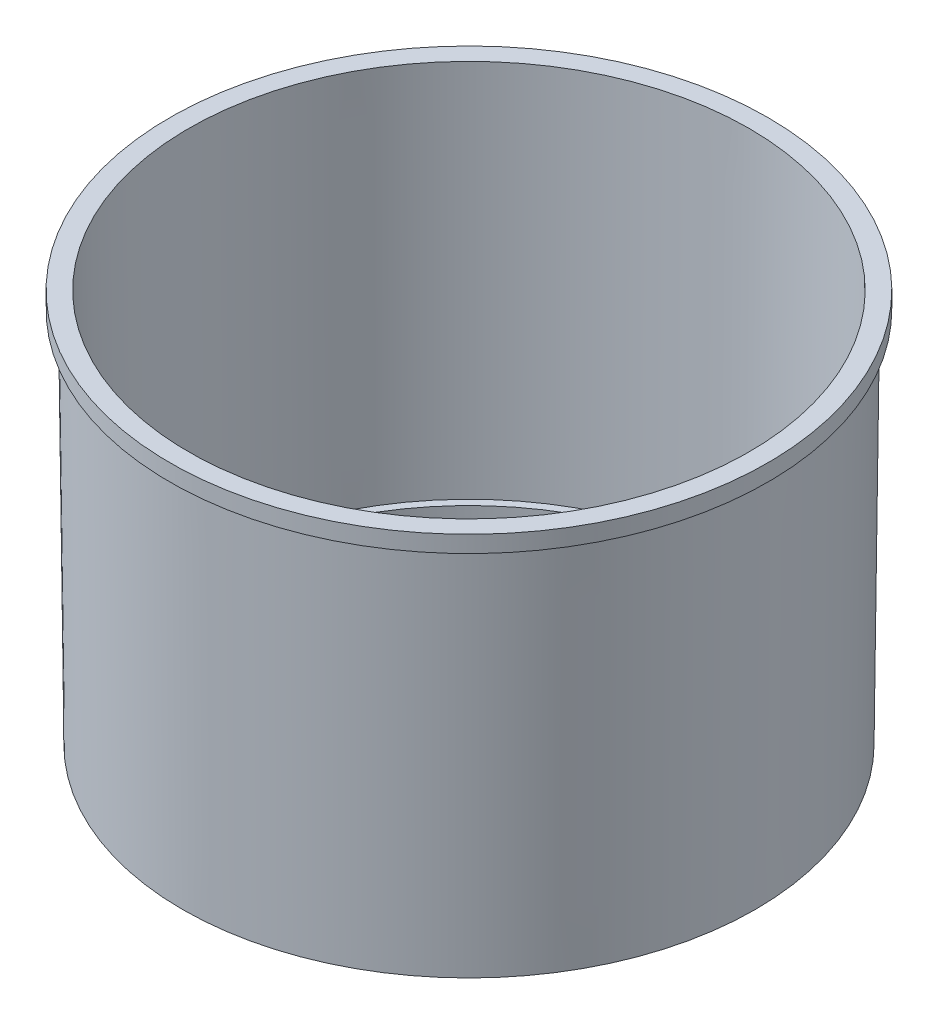
SolidWorks part; units mm, degrees
ref_plane "前视基准面" through (0, 0, 0) normal (0, 0, 1) x (1, 0, 0)
ref_plane "上视基准面" through (0, 0, 0) normal (0, 1, 0) x (1, 0, 0)
ref_plane "右视基准面" through (0, 0, 0) normal (1, 0, 0) x (0, 0, -1)
ref_axis "基准轴1" through (0, -2.25, 0) along (0, 1, 0)
ref_plane "基准面1" through (0, 47, 0) normal (0, 1, 0) x (1, 0, 0)
sketch "草图3" plane through (0, 0, 0) normal (0, 0, 1) x (1, 0, 0)
  line L0 (-34.7288, 45) -> (-34.25, 0)
  line L1 (55, 47) -> (-55, 47) construction
  line L2 (55, 0) -> (-55, 0) construction
  line L4 (-33.0212, 2) -> (-33.5, 47)
  line L6 (0, -55) -> (0, 55) construction
  line L7 (-33.0212, 2) -> (-32.1, 2)
  line L8 (-32.1, 2) -> (-32.1, 0)
  line L11 (-35.75, 47) -> (-35.75, 45)
  line L12 (-35.75, 45) -> (-34.7288, 45)
  line L13 (-32.1, 0) -> (-34.25, 0)
  line L15 (-35.75, 47) -> (-33.5, 47)
  dimension "D2" = 1.25
  dimension "D3" = 34.25
  dimension "D4" = 2
  dimension "D5" = 32.1
revolve "旋转1" add sketch "草图3" angle 360 about axis through (0, -2.25, 0) along (0, 1, 0)
